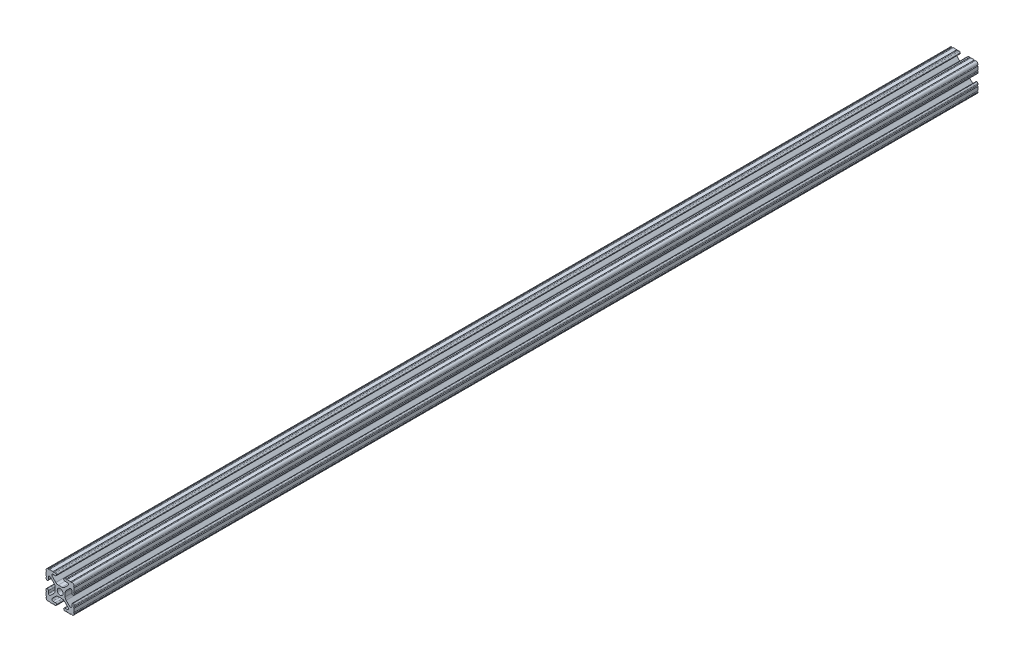
SolidWorks part; units mm, degrees
ref_plane "Front Plane" through (0, 0, 0) normal (0, 0, 1) x (1, 0, 0)
ref_plane "Top Plane" through (0, 0, 0) normal (0, 1, 0) x (1, 0, 0)
ref_plane "Right Plane" through (0, 0, 0) normal (1, 0, 0) x (0, 0, -1)
sketch "Sketch1" plane through (0, 0, 0) normal (0, 0, 1) x (1, 0, 0)
  line L88 (-7.1797, -8.6452) -> (-3.9523, -5.4237)
  line L89 (-1.7093, -4.4958) -> (1.7093, -4.4958)
  line L90 (3.9523, -5.4237) -> (7.1797, -8.6452)
  line L91 (6.4164, -10.4902) -> (4.2875, -10.4902)
  line L92 (3.2385, -11.5392) -> (3.2385, -11.651)
  line L93 (4.2875, -12.7) -> (5.3171, -12.7)
  line L94 (6.3331, -12.7) -> (9.5504, -12.7)
  line L95 (12.7, -9.5504) -> (12.7, -6.3331)
  line L96 (12.7, -5.3171) -> (12.7, -4.2875)
  line L97 (11.651, -3.2385) -> (11.5392, -3.2385)
  line L98 (10.4902, -4.2875) -> (10.4902, -6.4021)
  line L99 (8.7371, -7.1294) -> (5.441, -3.8408)
  line L100 (4.5085, -1.5932) -> (4.5085, 1.5932)
  line L101 (5.441, 3.8408) -> (8.7371, 7.1294)
  line L102 (10.4902, 6.4021) -> (10.4902, 4.2875)
  line L103 (11.5392, 3.2385) -> (11.651, 3.2385)
  line L104 (12.7, 4.2875) -> (12.7, 5.3171)
  line L105 (12.7, 6.3331) -> (12.7, 9.5504)
  line L106 (9.5504, 12.7) -> (6.3331, 12.7)
  line L107 (5.3171, 12.7) -> (4.2875, 12.7)
  line L108 (3.2385, 11.651) -> (3.2385, 11.5392)
  line L109 (4.2875, 10.4902) -> (6.4768, 10.4902)
  line L110 (7.207, 8.7244) -> (3.8983, 5.4232)
  line L111 (1.6558, 4.4958) -> (-1.6558, 4.4958)
  line L112 (-3.8983, 5.4232) -> (-7.207, 8.7244)
  line L113 (-6.4768, 10.4902) -> (-4.2875, 10.4902)
  line L114 (-3.2385, 11.5392) -> (-3.2385, 11.651)
  line L115 (-4.2875, 12.7) -> (-5.3171, 12.7)
  line L116 (-6.3331, 12.7) -> (-9.5504, 12.7)
  line L117 (-12.7, 9.5504) -> (-12.7, 6.3331)
  line L118 (-12.7, 5.3171) -> (-12.7, 4.2875)
  line L119 (-11.651, 3.2385) -> (-11.5392, 3.2385)
  line L120 (-10.4902, 4.2875) -> (-10.4902, 6.4021)
  line L121 (-8.7371, 7.1294) -> (-5.441, 3.8408)
  line L122 (-4.5085, 1.5932) -> (-4.5085, -1.5932)
  line L123 (-5.441, -3.8408) -> (-8.7371, -7.1294)
  line L124 (-10.4902, -6.4021) -> (-10.4902, -4.2875)
  line L125 (-11.5392, -3.2385) -> (-11.651, -3.2385)
  line L126 (-12.7, -4.2875) -> (-12.7, -5.3171)
  line L127 (-12.7, -6.3331) -> (-12.7, -9.5504)
  line L128 (-9.5504, -12.7) -> (-6.3331, -12.7)
  line L129 (-5.3171, -12.7) -> (-4.2875, -12.7)
  line L130 (-3.2385, -11.651) -> (-3.2385, -11.5392)
  line L131 (-4.2875, -10.4902) -> (-6.4164, -10.4902)
  circle A1 centre (0, 0) radius 2.6035
  arc A104 (-7.1797, -8.6452) -> (-6.4164, -10.4902) centre (-6.4164, -9.4098) ccw
  arc A105 (-1.7093, -4.4958) -> (-3.9523, -5.4237) centre (-1.7093, -7.6708) ccw
  arc A106 (3.9523, -5.4237) -> (1.7093, -4.4958) centre (1.7093, -7.6708) ccw
  arc A107 (6.4164, -10.4902) -> (7.1797, -8.6452) centre (6.4164, -9.4098) ccw
  arc A108 (4.2875, -10.4902) -> (3.2385, -11.5392) centre (4.2875, -11.5392) ccw
  arc A109 (3.2385, -11.651) -> (4.2875, -12.7) centre (4.2875, -11.651) ccw
  arc A110 (6.3331, -12.7) -> (5.3171, -12.7) centre (5.8251, -12.7) ccw
  arc A111 (10.5664, -12.6998) -> (9.5504, -12.7) centre (10.0584, -12.7) ccw
  arc A112 (10.5664, -12.6998) -> (12.6998, -10.5664) centre (10.5918, -10.5918) ccw
  arc A113 (12.7, -9.5504) -> (12.6998, -10.5664) centre (12.7, -10.0584) ccw
  arc A114 (12.7, -5.3171) -> (12.7, -6.3331) centre (12.7, -5.8251) ccw
  arc A115 (12.7, -4.2875) -> (11.651, -3.2385) centre (11.651, -4.2875) ccw
  arc A116 (11.5392, -3.2385) -> (10.4902, -4.2875) centre (11.5392, -4.2875) ccw
  arc A117 (8.7371, -7.1294) -> (10.4902, -6.4021) centre (9.4628, -6.4021) ccw
  arc A118 (4.5085, -1.5932) -> (5.441, -3.8408) centre (7.6835, -1.5932) ccw
  arc A119 (5.441, 3.8408) -> (4.5085, 1.5932) centre (7.6835, 1.5932) ccw
  arc A120 (10.4902, 6.4021) -> (8.7371, 7.1294) centre (9.4628, 6.4021) ccw
  arc A121 (10.4902, 4.2875) -> (11.5392, 3.2385) centre (11.5392, 4.2875) ccw
  arc A122 (11.651, 3.2385) -> (12.7, 4.2875) centre (11.651, 4.2875) ccw
  arc A123 (12.7, 6.3331) -> (12.7, 5.3171) centre (12.7, 5.8251) ccw
  arc A124 (12.6998, 10.5664) -> (12.7, 9.5504) centre (12.7, 10.0584) ccw
  arc A125 (12.6998, 10.5664) -> (10.5664, 12.6998) centre (10.5918, 10.5918) ccw
  arc A126 (9.5504, 12.7) -> (10.5664, 12.6998) centre (10.0584, 12.7) ccw
  arc A127 (5.3171, 12.7) -> (6.3331, 12.7) centre (5.8251, 12.7) ccw
  arc A128 (4.2875, 12.7) -> (3.2385, 11.651) centre (4.2875, 11.651) ccw
  arc A129 (3.2385, 11.5392) -> (4.2875, 10.4902) centre (4.2875, 11.5392) ccw
  arc A130 (7.207, 8.7244) -> (6.4768, 10.4902) centre (6.4768, 9.4563) ccw
  arc A131 (1.6558, 4.4958) -> (3.8983, 5.4232) centre (1.6558, 7.6708) ccw
  arc A132 (-3.8983, 5.4232) -> (-1.6558, 4.4958) centre (-1.6558, 7.6708) ccw
  arc A133 (-6.4768, 10.4902) -> (-7.207, 8.7244) centre (-6.4768, 9.4563) ccw
  arc A134 (-4.2875, 10.4902) -> (-3.2385, 11.5392) centre (-4.2875, 11.5392) ccw
  arc A135 (-3.2385, 11.651) -> (-4.2875, 12.7) centre (-4.2875, 11.651) ccw
  arc A136 (-6.3331, 12.7) -> (-5.3171, 12.7) centre (-5.8251, 12.7) ccw
  arc A137 (-10.5664, 12.6998) -> (-9.5504, 12.7) centre (-10.0584, 12.7) ccw
  arc A138 (-10.5664, 12.6998) -> (-12.6998, 10.5664) centre (-10.5918, 10.5918) ccw
  arc A139 (-12.7, 9.5504) -> (-12.6998, 10.5664) centre (-12.7, 10.0584) ccw
  arc A140 (-12.7, 5.3171) -> (-12.7, 6.3331) centre (-12.7, 5.8251) ccw
  arc A141 (-12.7, 4.2875) -> (-11.651, 3.2385) centre (-11.651, 4.2875) ccw
  arc A142 (-11.5392, 3.2385) -> (-10.4902, 4.2875) centre (-11.5392, 4.2875) ccw
  arc A143 (-8.7371, 7.1294) -> (-10.4902, 6.4021) centre (-9.4628, 6.4021) ccw
  arc A144 (-4.5085, 1.5932) -> (-5.441, 3.8408) centre (-7.6835, 1.5932) ccw
  arc A145 (-5.441, -3.8408) -> (-4.5085, -1.5932) centre (-7.6835, -1.5932) ccw
  arc A146 (-10.4902, -6.4021) -> (-8.7371, -7.1294) centre (-9.4628, -6.4021) ccw
  arc A147 (-10.4902, -4.2875) -> (-11.5392, -3.2385) centre (-11.5392, -4.2875) ccw
  arc A148 (-11.651, -3.2385) -> (-12.7, -4.2875) centre (-11.651, -4.2875) ccw
  arc A149 (-12.7, -6.3331) -> (-12.7, -5.3171) centre (-12.7, -5.8251) ccw
  arc A150 (-12.6998, -10.5664) -> (-12.7, -9.5504) centre (-12.7, -10.0584) ccw
  arc A151 (-12.6998, -10.5664) -> (-10.5664, -12.6998) centre (-10.5918, -10.5918) ccw
  arc A152 (-9.5504, -12.7) -> (-10.5664, -12.6998) centre (-10.0584, -12.7) ccw
  arc A153 (-5.3171, -12.7) -> (-6.3331, -12.7) centre (-5.8251, -12.7) ccw
  arc A154 (-4.2875, -12.7) -> (-3.2385, -11.651) centre (-4.2875, -11.651) ccw
  arc A155 (-3.2385, -11.5392) -> (-4.2875, -10.4902) centre (-4.2875, -11.5392) ccw
extrude "Boss-Extrude1" add sketch "Sketch1" along normal mid plane 812.8
